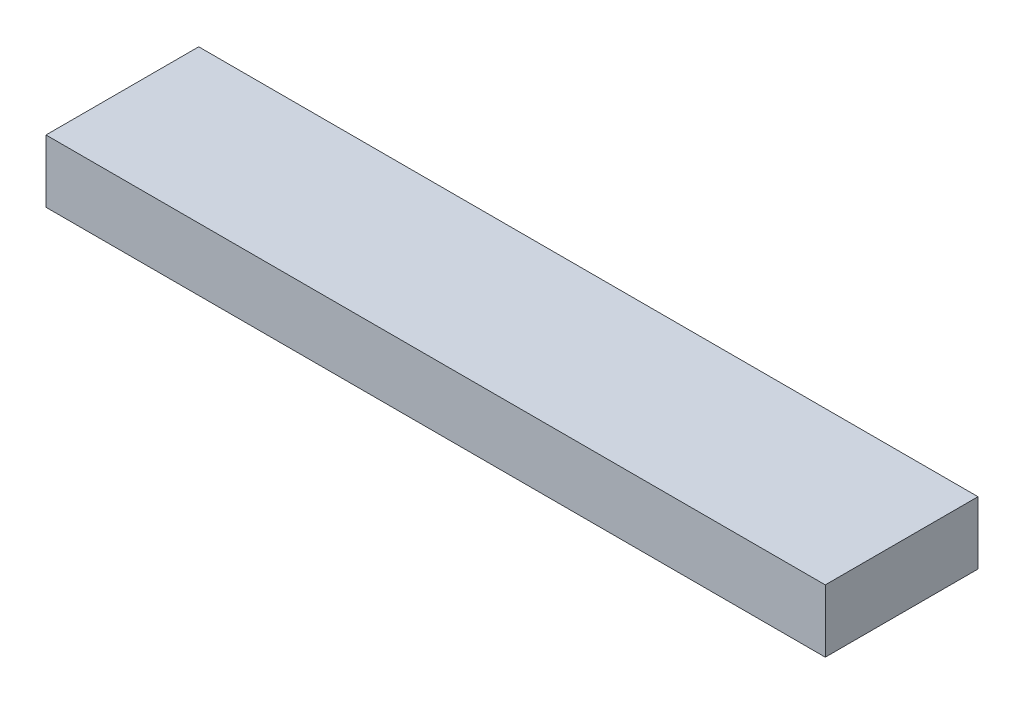
SolidWorks part; units mm, degrees
ref_plane "Спереди" through (0, 0, 0) normal (0, 0, 1) x (1, 0, 0)
ref_plane "Сверху" through (0, 0, 0) normal (0, 1, 0) x (1, 0, 0)
ref_plane "Справа" through (0, 0, 0) normal (1, 0, 0) x (0, 0, -1)
sketch "Эскиз1" plane through (0, 0, 0) normal (0, 1, 0) x (1, 0, 0)
  line L1 (19.9, -3.9) -> (-19.9, -3.9)
  line L2 (19.9, -3.9) -> (19.9, 3.9)
  line L3 (19.9, 3.9) -> (-19.9, 3.9)
  line L4 (-19.9, -3.9) -> (-19.9, 3.9)
  line L5 (19.9, -3.9) -> (-19.9, 3.9) construction
  line L6 (19.9, 3.9) -> (-19.9, -3.9) construction
  circle A0 centre (16, 0) radius 2.5
  circle A1 centre (8.126, 0) radius 2.5
  circle A2 centre (0.252, 0) radius 2.5
  circle A3 centre (-7.622, 0) radius 2.5
  circle A4 centre (-15.496, 0) radius 2.5
  point P0 (0, 0)
  dimension "D5" = 5
  dimension "D1" = 39.8
  dimension "D2" = 7.8
  dimension "D3" = 3.9
  dimension "D4" = 3.9
extrude "Бобышка-Вытянуть1" add sketch "Эскиз1" along normal blind 3.2 contours L2 L1 L4 L3
sketch "Эскиз2" plane through (0, 0, 0) normal (0, -1, 0) x (1, 0, 0)
  line L0 (19.9, -3.9) -> (-19.9, -3.9) construction
  line L1 (19.9, 3.9) -> (19.9, -3.9) construction
  circle A0 centre (16, 0) radius 2.5
  circle A1 centre (8.126, 0) radius 2.5
  circle A2 centre (0.252, 0) radius 2.5
  circle A3 centre (-7.622, 0) radius 2.5
  circle A4 centre (-15.496, 0) radius 2.5
  dimension "D3" = 5
  dimension "D1" = 3.9
  dimension "D2" = 3.9
extrude "Вырез-Вытянуть1" cut sketch "Эскиз2" against normal blind 1.8
